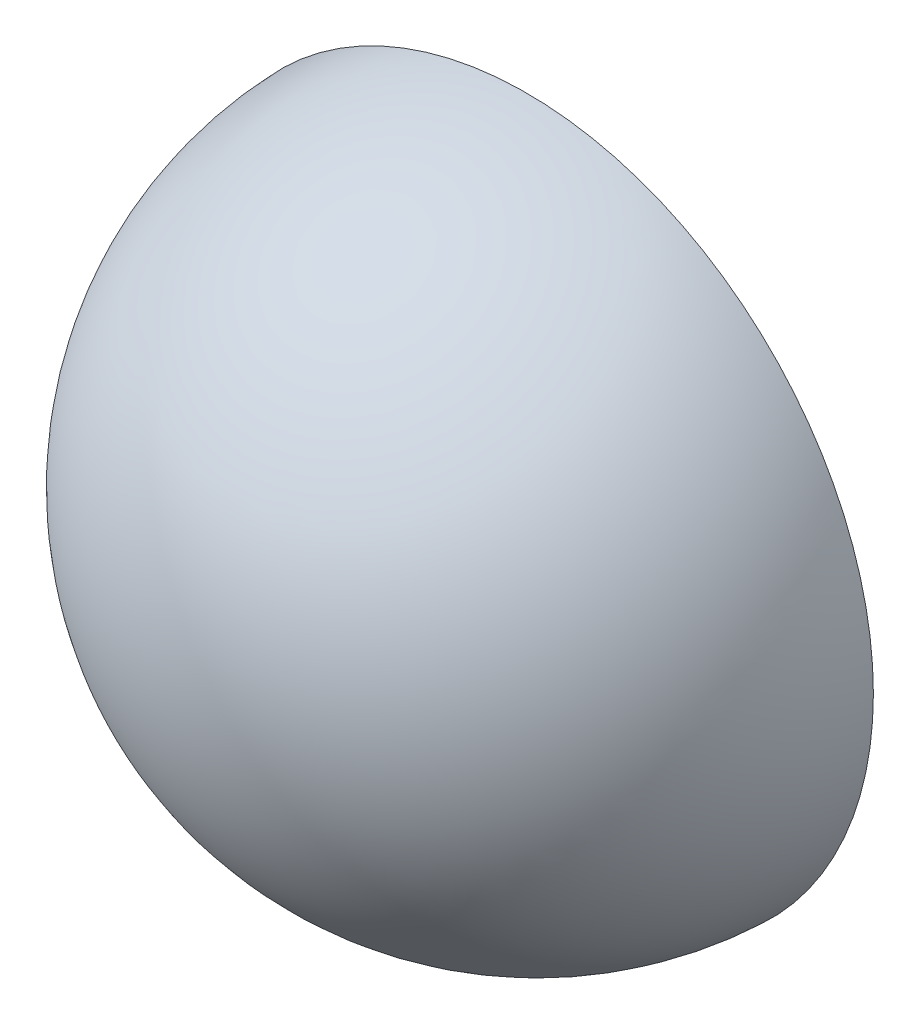
SolidWorks part; units mm, degrees
ref_plane "前视基准面" through (0, 0, 0) normal (0, 0, 1) x (1, 0, 0)
ref_plane "上视基准面" through (0, 0, 0) normal (0, 1, 0) x (1, 0, 0)
ref_plane "右视基准面" through (0, 0, 0) normal (1, 0, 0) x (0, 0, -1)
other "Configuration Table"
sketch "草图2" plane through (0, 0, 0) normal (0, 1, 0) x (1, 0, 0)
  line L0 (0, 0) -> (0, 11.6998) construction
  line L11 (0, -71.415) -> (0, -71.9301)
  line L12 (10.4872, -60.9278) -> (11.3366, -60.9278)
  arc A14 (11.3366, -60.9278) -> (0, -71.9301) centre (0, -60.5884) cw
  arc A15 (10.4872, -60.9278) -> (0, -71.415) centre (0, -60.9278) cw
revolve "旋转1" add sketch "草图2" angle 360 about L0
